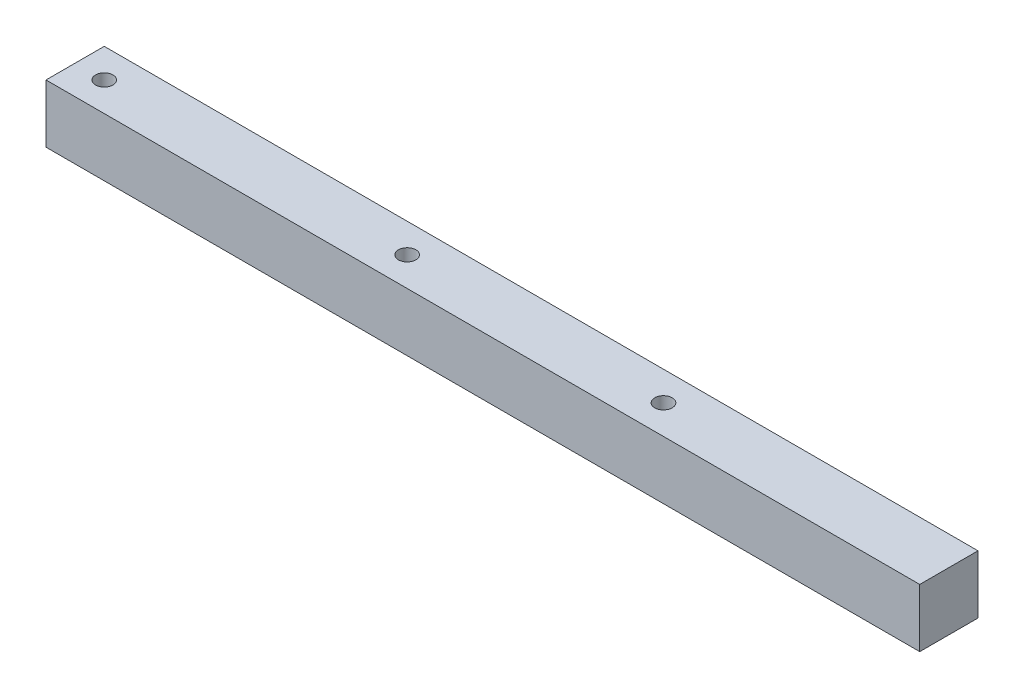
SolidWorks part; units mm, degrees
ref_plane "Front" through (0, 0, 0) normal (0, 0, 1) x (1, 0, 0)
ref_plane "Top" through (0, 0, 0) normal (0, 1, 0) x (1, 0, 0)
ref_plane "Right" through (0, 0, 0) normal (1, 0, 0) x (0, 0, -1)
sketch "Skizze1" plane through (0, 0, 0) normal (1, 0, 0) x (0, 0, -1)
  line L1 (-10, -10) -> (10, -10)
  line L2 (-10, -10) -> (-10, 10)
  line L3 (-10, 10) -> (10, 10)
  line L4 (10, -10) -> (10, 10)
  line L5 (-10, -10) -> (10, 10) construction
  line L6 (-10, 10) -> (10, -10) construction
  point P0 (0, 0)
  dimension "D1" = 20
extrude "Aufsatz-Linear austragen1" add sketch "Skizze1" along normal blind 300
sketch "Skizze2" plane through (0, 10, 0) normal (0, 1, 0) x (1, 0, 0)
  line L0 (0, 0) -> (300, 0) construction
  line L1 (0, 10) -> (0, -10) construction
  line L2 (300, 10) -> (300, -10) construction
  line L3 (150, 0) -> (150, 10) construction
  line L4 (300, 10) -> (0, 10) construction
  circle A0 centre (10, 0) radius 3
  circle A2 centre (114, 0) radius 3
  circle A3 centre (202, 0) radius 3
  dimension "D2" = 6
  dimension "D1" = 10
  dimension "D3" = 114
  dimension "D4" = 202
extrude "Schnitt-Linear austragen1" cut sketch "Skizze2" against normal through all
